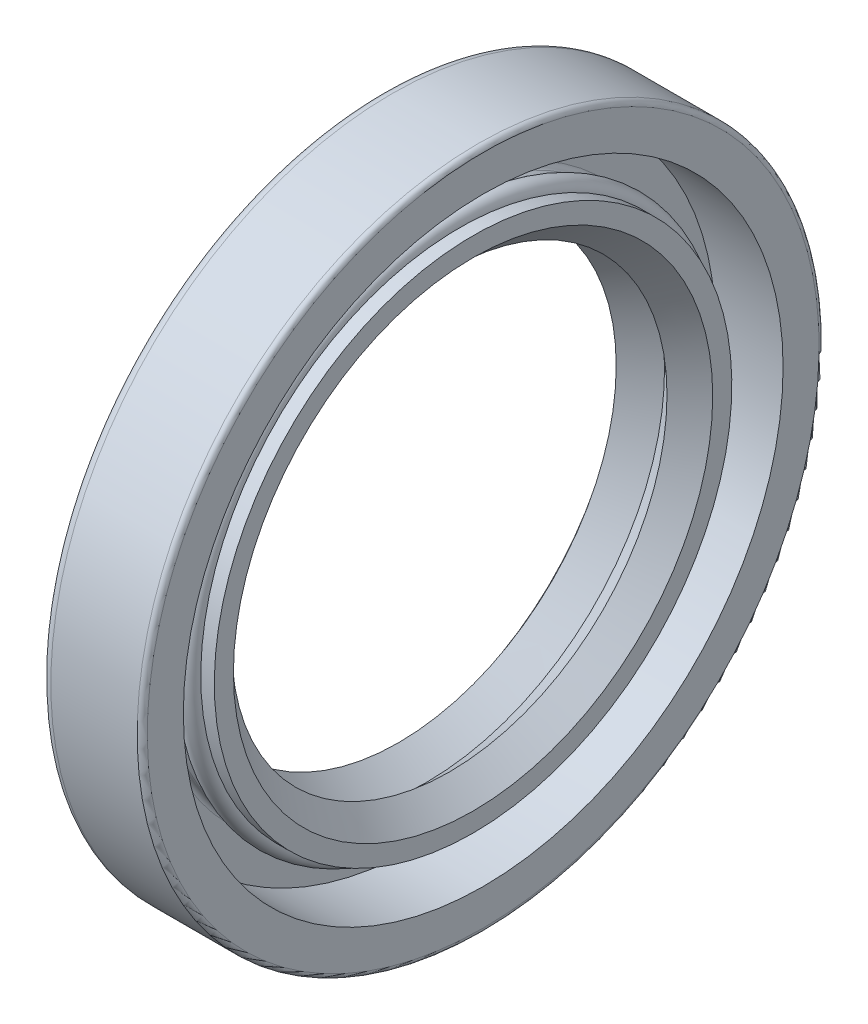
SolidWorks part; units mm, degrees
ref_plane "Front" through (0, 0, 0) normal (0, 0, 1) x (1, 0, 0)
ref_plane "Top" through (0, 0, 0) normal (0, 1, 0) x (1, 0, 0)
ref_plane "Right" through (0, 0, 0) normal (1, 0, 0) x (0, 0, -1)
sketch "Sketch1" plane through (0, 0, 0) normal (0, 0, 1) x (1, 0, 0)
  line L0 (0, 20.6667) -> (0.2188, 20.6667)
  line L1 (0.2188, 20.6667) -> (0.2188, 17.8333)
  line L2 (0.2188, 17.8333) -> (0, 17.8333)
  line L3 (0, 17.8333) -> (0, 17.125)
  line L4 (0, 17.125) -> (1.1667, 16.4167)
  line L5 (1.1667, 16.4167) -> (0.4891, 15.915)
  line L6 (0.4891, 15.915) -> (1.1667, 15)
  line L7 (1.1667, 15) -> (3.0798, 16.4167)
  line L8 (3.0798, 16.4167) -> (4.6667, 15)
  line L9 (4.6667, 15) -> (6.3, 16.5167)
  line L10 (6.3, 16.5167) -> (6.3, 17.8333)
  line L11 (6.3, 17.8333) -> (5.3667, 17.8333)
  line L12 (3.9667, 17.8333) -> (2.6833, 17.8333)
  line L13 (2.3333, 18.1833) -> (2.3333, 20.6667)
  line L14 (2.3333, 20.6667) -> (7, 20.6667)
  line L15 (7, 20.6667) -> (7, 23.15)
  line L16 (6.65, 23.5) -> (0.7, 23.5)
  line L17 (0, 22.8) -> (0, 20.6667)
  line L18 (7, 0) -> (0, 0) construction
  line L19 (1.1667, 15) -> (4.6667, 15) construction
  line L20 (3.675, 23.5) -> (3.675, 20.6667) construction
  line L21 (3.675, 20.6667) -> (3.675, 17.8333) construction
  line L22 (3.675, 17.8333) -> (3.675, 15) construction
  line L23 (4.6667, 17.8333) -> (4.6667, 15) construction
  line L24 (0, 21.7333) -> (2.3333, 21.7333) construction
  line L25 (2.3333, 21.7333) -> (4.6667, 21.7333) construction
  line L26 (4.6667, 21.7333) -> (7, 21.7333) construction
  line L27 (4.6667, 17.8333) -> (4.6667, 21.7333) construction
  line L28 (2.3333, 18.1833) -> (3.0798, 16.4167) construction
  line L29 (3.675, 16.4167) -> (3.0798, 16.4167) construction
  line L30 (3.3774, 16.4167) -> (3.3774, 17.8333) construction
  line L31 (3.3774, 17.125) -> (0, 17.125) construction
  line L32 (3.0798, 16.4167) -> (1.1667, 16.4167) construction
  line L33 (1.1667, 15) -> (1.1667, 16.4167) construction
  line L35 (7, 20.6667) -> (7, 17.8333) construction
  line L36 (7, 17.8333) -> (6.3, 17.8333) construction
  line L37 (0, 22.8) -> (0.7, 22.8) construction
  line L39 (1.1667, 21.7333) -> (1.1667, 16.4167) construction
  arc A0 (5.3667, 17.8333) -> (3.9667, 17.8333) centre (4.6667, 17.8333) ccw construction
  arc A1 (2.6833, 17.8333) -> (2.3333, 18.1833) centre (2.6833, 18.1833) cw
  arc A2 (7, 23.15) -> (6.65, 23.5) centre (6.65, 23.15) ccw
  arc A3 (0.7, 23.5) -> (0, 22.8) centre (0.7, 22.8) ccw
  arc A4 (3.9667, 17.8333) -> (5.3667, 17.8333) centre (4.6667, 17.8333) ccw
  dimension "D3" = 0.7
  dimension "D4" = 0.35
  dimension "D2" = 0.2188
  dimension "D5" = 67.784
  dimension "D8" = 47.121
revolve "Revolve1" add sketch "Sketch1" angle 360 about L18
sketch "Sketch2" plane through (0, 0, 0) normal (0, 0, 1) x (1, 0, 0)
  line L0 (0, 0) -> (7, 0) construction
  circle A0 centre (4.6667, 17.8333) radius 0.7
revolve "Revolve2" add sketch "Sketch2" angle 360 about L0
equation "\"D2@Sketch1\"=\"SealWidth@Sketch1\"*.03125"
equation "\"D3@Sketch1\"=\"SealWidth@Sketch1\"*.1"
equation "\"D4@Sketch1\"=\"D3@Sketch1\"*.5"
